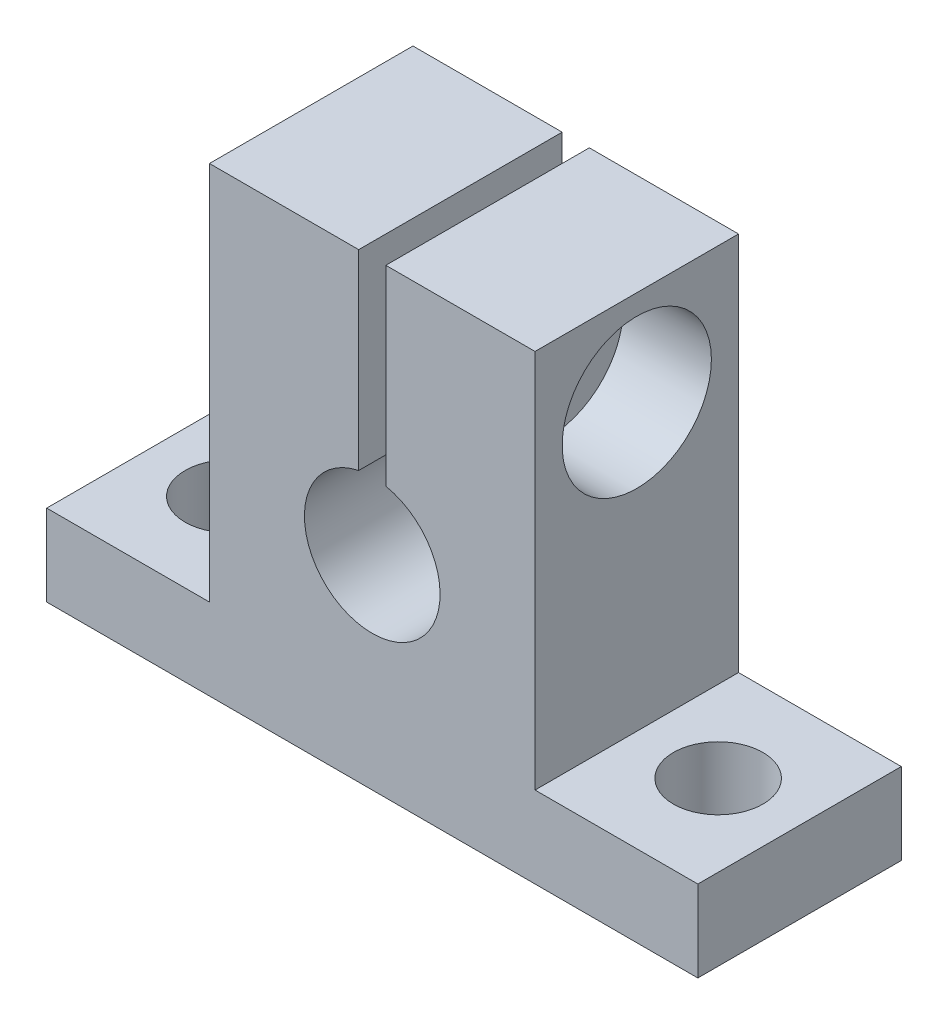
SolidWorks part; units mm, degrees
ref_plane "Front Plane" through (0, 0, 0) normal (0, 0, 1) x (1, 0, 0)
ref_plane "Top Plane" through (0, 0, 0) normal (0, 1, 0) x (1, 0, 0)
ref_plane "Right Plane" through (0, 0, 0) normal (1, 0, 0) x (0, 0, -1)
sketch "Sketch1" plane through (0, 0, 0) normal (0, 0, 1) x (1, 0, 0)
  line L0 (-24, 0) -> (24, 0)
  line L1 (24, 0) -> (24, 6)
  line L2 (24, 6) -> (12, 6)
  line L3 (12, 6) -> (12, 34)
  line L4 (12, 34) -> (-12, 34)
  line L5 (-12, 34) -> (-12, 6)
  line L6 (-12, 6) -> (-24, 6)
  line L7 (-24, 6) -> (-24, 0)
  line L8 (0, 0) -> (0, 34) construction
  line L9 (-12, 15) -> (12, 15) construction
  dimension "L" = 48
  dimension "S" = 6
  dimension "W" = 24
  dimension "H1" = 34
  dimension "H" = 15
  dimension "MSM_1" = 19
extrude "Boss-Extrude1" add sketch "Sketch1" along normal mid plane 15
sketch "Sketch2" plane through (0, 0, 7.5) normal (0, 0, 1) x (1, 0, 0)
  line L0 (0, 0) -> (0, 15) construction
  circle A0 centre (0, 15) radius 5
  dimension "H" = 15
  dimension "D" = 10
extrude "Cut-Extrude1" cut sketch "Sketch2" against normal through all
sketch "Sketch3" plane through (0, 0, 7.5) normal (0, 0, 1) x (1, 0, 0)
  line L0 (0, 0) -> (0, 34) construction
  line L1 (-1, 34) -> (1, 34)
  line L2 (-1, 34) -> (-1, 15)
  line L3 (-1, 15) -> (1, 15)
  line L4 (1, 34) -> (1, 15)
  line L5 (12, 34) -> (-12, 34) construction
  dimension "C" = 2
  dimension "H" = 15
extrude "Cut-Extrude2" cut sketch "Sketch3" against normal through all
hole_wizard "CBORE for Socket Head Cap Screw1" positions "Sketch5" profile "Sketch4" counterbore size "M6" standard "JIS"
sketch "Sketch5" plane through (12, 0, 0) normal (1, 0, 0) x (0, 0, -1)
  line L0 (-7.5, 15) -> (7.5, 15) construction
  line L1 (-7.5, 6) -> (-7.5, 34) construction
  line L2 (7.5, 6) -> (7.5, 34) construction
  line L3 (0, 0) -> (0, 34) construction
  line L4 (-7.5, 34) -> (7.5, 34) construction
  point P0 (0, 27)
  dimension "H" = 15
  dimension "E" = 12
sketch "Sketch4" plane through (12, 27, 0) normal (0, 1, 0) x (0, 0, -1)
  line L0 (0, 0) -> (0, 11)
  line L1 (0, 11) -> (3.3, 11)
  line L3 (3.3, 11) -> (3.3, 6.5)
  line L4 (3.3, 6.5) -> (5.5, 6.5)
  line L5 (5.5, 6.5) -> (5.5, 0)
  line L7 (5.5, 0) -> (0, 0)
  line L11 (0, 0) -> (0, 11) construction
  dimension "D2_s" = 6.6
  dimension "Thru Hole Depth" = 11
  dimension "D1_s" = 11
  dimension "L_s" = 6.5
hole_wizard "Tapped Hole1" positions "Sketch7" profile "Sketch6" tap size "M6x1.0" standard "JIS" end condition through all
sketch "Sketch7" plane through (-1, 0, 0) normal (1, 0, 0) x (0, 0, -1)
  point P0 (0, 27)
sketch "Sketch6" plane through (-1, 27, 0) normal (0, 1, 0) x (0, 0, -1)
  line L0 (0, 0) -> (0, 23)
  line L1 (0, 23) -> (2.5, 23)
  line L2 (2.5, 23) -> (2.5, 0)
  line L5 (2.5, 0) -> (0, 0)
  line L11 (0, -6.35) -> (0, 107.95) construction
  dimension "Thru Tap Drill Dia." = 5
  dimension "Thru Tap Drill Depth" = 23
cosmetic thread "Hole Thread1" parameters "M"=6
hole_wizard "Diameter Hole1" positions "Sketch9" profile "Sketch8" hole size "Ø6.6" standard "JIS" end condition through all
sketch "Sketch9" plane through (0, 6, 0) normal (0, 1, 0) x (1, 0, 0)
  line L0 (0, 0) -> (0, -7.5) construction
  line L2 (24, -7.5) -> (-24, -7.5) construction
  line L3 (-24, 0) -> (24, 0) construction
  line L5 (24, -7.5) -> (24, 7.5) construction
  line L6 (-24, -7.5) -> (-24, 7.5) construction
  point P0 (18, 0)
  point P2 (-18, 0)
  dimension "L1" = 36
sketch "Sketch8" plane through (18, 6, 0) normal (1, 0, 0) x (0, 0, 1)
  line L0 (0, 0) -> (0, 6)
  line L1 (0, 6) -> (3.3, 6)
  line L2 (3.3, 6) -> (3.3, 0)
  line L5 (3.3, 0) -> (0, 0)
  line L11 (0, 0) -> (0, 6) construction
  dimension "D_s" = 6.6
  dimension "Thru Hole Depth" = 6
hole_wizard "CBORE for Socket Head Cap Screw2" positions "Sketch11" profile "Sketch10" counterbore size "M8" standard "JIS"
sketch "Sketch11" plane through (30, 0, 0) normal (1, 0, 0) x (0, 0, -1)
  line L0 (-17.5, 30) -> (17.5, 30) construction
  line L1 (-17.5, 10) -> (-17.5, 68) construction
  line L2 (17.5, 10) -> (17.5, 68) construction
  line L3 (0, 0) -> (0, 68) construction
  line L4 (-17.5, 68) -> (17.5, 68) construction
  point P0 (8.75, 59)
  point P13 (-8.75, 59)
  dimension "H" = 15
  dimension "E" = 12
  dimension "D1" = 7.5
sketch "Sketch10" plane through (30, 59, -8.75) normal (0, 1, 0) x (0, 0, -1)
  line L0 (0, 0) -> (0, 28.5)
  line L1 (0, 28.5) -> (3.3, 28.5)
  line L3 (3.3, 28.5) -> (3.3, 6.5)
  line L4 (3.3, 6.5) -> (5.5, 6.5)
  line L5 (5.5, 6.5) -> (5.5, 0)
  line L7 (5.5, 0) -> (0, 0)
  line L11 (0, 0) -> (0, 28.5) construction
  dimension "D2_s" = 6.6
  dimension "Thru Hole Depth" = 28.5
  dimension "D1_s" = 11
  dimension "L_s" = 6.5
hole_wizard "Tapped Hole2" positions "Sketch13" profile "Sketch12" tap size "M8x1.25" standard "JIS"
sketch "Sketch13" plane through (-1.5, 0, 0) normal (1, 0, 0) x (0, 0, -1)
  circle A2 centre (-8.75, 49) radius 3.3 construction
  circle A3 centre (8.75, 49) radius 3.3 construction
  point P0 (-8.75, 49)
  point P3 (8.75, 49)
sketch "Sketch12" plane through (-1.5, 49, 8.75) normal (0, 1, 0) x (0, 0, -1)
  line L0 (0, 0) -> (0, 41)
  line L1 (0, 41) -> (3.4, 41)
  line L2 (3.4, 41) -> (3.4, 0)
  line L5 (3.4, 0) -> (0, 0)
  line L11 (0, 0) -> (0, 41) construction
  dimension "Thru Tap Drill Dia." = 6.8
  dimension "Thru Tap Drill Depth" = 41
cosmetic thread "Hole Thread18"
cosmetic thread "Hole Thread19"
hole_wizard "Tapped Hole3" positions "Sketch15" profile "Sketch14" tap size "M8x1.25" standard "JIS"
sketch "Sketch15" plane through (-1.5, 0, 0) normal (1, 0, 0) x (0, 0, -1)
  circle A3 centre (-8.75, 59) radius 3.3 construction
  circle A4 centre (8.75, 59) radius 3.3 construction
  point P0 (8.75, 59)
  point P10 (-8.75, 59)
sketch "Sketch14" plane through (-1.5, 59, -8.75) normal (0, 1, 0) x (0, 0, -1)
  line L0 (0, 0) -> (0, 24.3429)
  line L1 (0, 24.3429) -> (3.4, 22.3)
  line L2 (3.4, 22.3) -> (3.4, 0)
  line L5 (3.4, 0) -> (0, 0)
  line L10 (0, 24.3429) -> (-3.4, 22.3) construction
  line L11 (0, 0) -> (0, 24.3429) construction
  dimension "Tap Drill Dia." = 6.8
  dimension "Tap Drill Depth" = 22.3
  dimension "Drill Angle" = 118
cosmetic thread "Hole Thread14"
cosmetic thread "Hole Thread15"
hole_wizard "Diameter Hole2" positions "Sketch17" profile "Sketch16" hole size "Ø6.6" standard "JIS"
sketch "Sketch17" plane through (0, 10, 0) normal (0, 1, 0) x (1, 0, 0)
  line L0 (0, 17.5) -> (0, -17.5) construction
  line L2 (-50, -17.5) -> (50, -17.5) construction
  line L3 (-50, 17.5) -> (50, 17.5) construction
  line L4 (-50, 0) -> (50, 0) construction
  line L6 (-50, -17.5) -> (-50, 17.5) construction
  line L7 (50, -17.5) -> (50, 17.5) construction
  point P0 (-18, 8.75)
  point P2 (18, 8.75)
  point P14 (-18, -8.75)
  point P16 (18, -8.75)
  dimension "D1" = 7.5
  dimension "L1" = 36
sketch "Sketch16" plane through (-18, 10, -8.75) normal (1, 0, 0) x (0, 0, 1)
  line L0 (0, 0) -> (0, 10)
  line L1 (0, 10) -> (3.3, 10)
  line L2 (3.3, 10) -> (3.3, 0)
  line L5 (3.3, 0) -> (0, 0)
  line L11 (0, 0) -> (0, 10) construction
  dimension "D_s" = 6.6
  dimension "Thru Hole Depth" = 10
equation "\"D1@Sketch11\" = \"T@Boss-Extrude1\" / 2"
equation "\"D1@Sketch17\"= \"T@Boss-Extrude1\" / 2"
equation "\"CBORE for Socket Head Cap Screw1\" = if ( \"D@Sketch2\" > 25 , \"suppressed\" , \"unsuppressed\" )"
equation "\"Tapped Hole1\" = if ( \"D@Sketch2\" > 25 , \"suppressed\" , \"unsuppressed\" )"
equation "\"Diameter Hole1\" = if ( \"D@Sketch2\" > 25 , \"suppressed\" , \"unsuppressed\" )"
equation "\"CBORE for Socket Head Cap Screw2\" = if ( \"D@Sketch2\" > 25 , \"unsuppressed\" , \"suppressed\" )"
equation "\"Tapped Hole2\"  = if ( \"D@Sketch2\" > 25 AND \"D@Sketch2\" < 40 , \"unsuppressed\" , \"suppressed\" )"
equation "\"Diameter Hole2\" = if ( \"D@Sketch2\" > 25 , \"unsuppressed\" , \"suppressed\" )"
equation "\"Tapped Hole3\" = if ( \"D@Sketch2\" > = 40 , \"unsuppressed\" , \"suppressed\" )"
